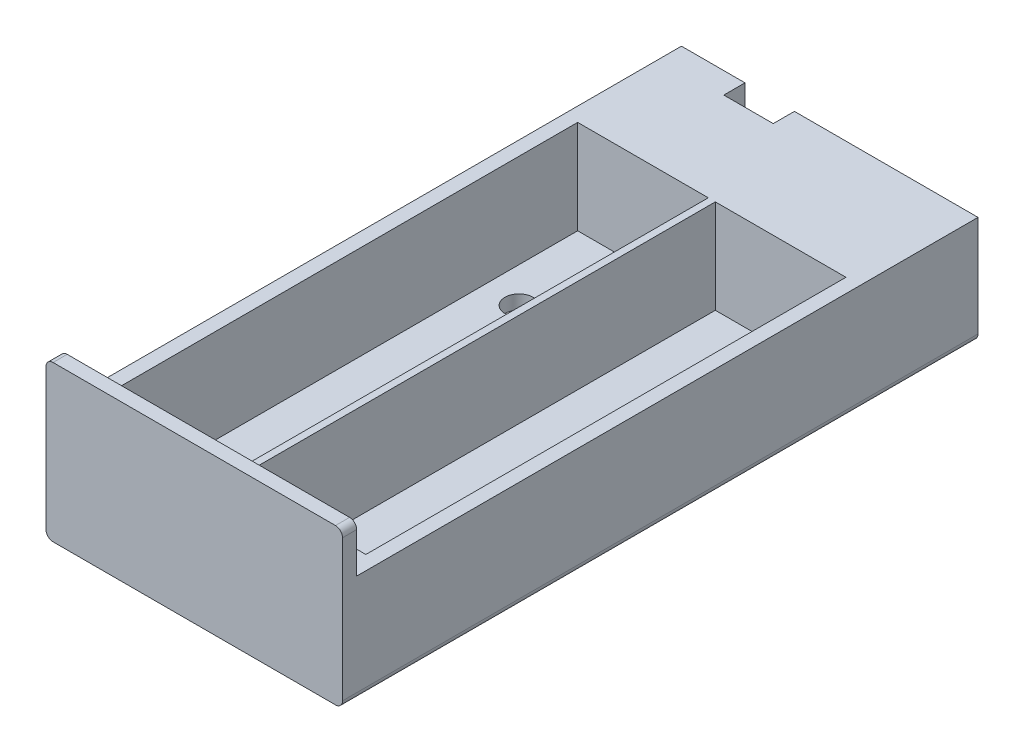
SolidWorks part; units mm, degrees
material "6061 Alloy"
ref_plane "Front" through (0, 0, 0) normal (0, 0, 1) x (1, 0, 0)
ref_plane "Top" through (0, 0, 0) normal (0, 1, 0) x (1, 0, 0)
ref_plane "Right" through (0, 0, 0) normal (1, 0, 0) x (0, 0, -1)
sketch "Sketch1" plane through (0, 0, 0) normal (0, 1, 0) x (1, 0, 0)
  line L1 (-21, -45) -> (21, -45)
  line L2 (-21, -45) -> (-21, 45)
  line L3 (-21, 45) -> (21, 45)
  line L4 (21, -45) -> (21, 45)
  line L5 (-21, -45) -> (21, 45) construction
  line L6 (-21, 45) -> (21, -45) construction
  point P0 (0, 0)
  dimension "D1" = 42
  dimension "D2" = 90
extrude "Boss-Extrude1" add sketch "Sketch1" along normal blind 22
fillet "Fillet1" radius 1 4 edges at (21, 0, 0) (-21, 0, 0) (21, 22, 0) (-21, 22, 0)
sketch "Sketch2" plane through (0, 22, 0) normal (0, 1, 0) x (1, 0, 0)
  line L0 (-20, -45) -> (20, -45) construction
  line L1 (-19, 28.3) -> (19, 28.3)
  line L2 (-19, 28.3) -> (-19, -39.7)
  line L3 (-19, -39.7) -> (19, -39.7)
  line L4 (19, 28.3) -> (19, -39.7)
  line L5 (-19, 28.3) -> (19, -39.7) construction
  line L6 (-19, -39.7) -> (19, 28.3) construction
  point P0 (0, -5.7)
  dimension "D1" = 38
  dimension "D2" = 68
  dimension "D3" = 5.3
extrude "Cut-Extrude1" cut sketch "Sketch2" against normal blind 20 contours L4 L1 L2 L3
sketch "Sketch3" plane through (0, 2, 0) normal (0, 1, 0) x (1, 0, 0)
  line L0 (-19, 28.3) -> (19, 28.3) construction
  line L1 (-0.5, 28.3) -> (0.5, 28.3)
  line L2 (-0.5, 28.3) -> (-0.5, -39.7)
  line L3 (-0.5, -39.7) -> (0.5, -39.7)
  line L4 (0.5, 28.3) -> (0.5, -39.7)
  line L5 (-19, -39.7) -> (19, -39.7) construction
  line L6 (0, 28.3) -> (0, -39.7) construction
  dimension "D1" = 1
extrude "Boss-Extrude2" add sketch "Sketch3" along normal up to surface (20 mm away) up to face at (0, 22, 0)
sketch "Sketch4" plane through (0, 22, 0) normal (0, 1, 0) x (1, 0, 0)
  line L0 (21, 45) -> (21, -45) construction
  line L1 (-21, 45) -> (21, 45)
  line L2 (-21, 45) -> (-21, -43)
  line L3 (-21, -43) -> (21, -43)
  line L4 (21, 45) -> (21, -43)
  line L5 (-20, -45) -> (20, -45) construction
  dimension "D1" = 2
extrude "Cut-Extrude2" cut sketch "Sketch4" against normal blind 6.7
sketch "Sketch5" plane through (0, 0, -45) normal (0, 0, -1) x (-1, 0, 0)
  line L0 (-21, 15.3) -> (-21, 1) construction
  line L1 (-20, 0) -> (20, 0) construction
  circle A0 centre (-13.5, 3.5) radius 1.5
  dimension "D3" = 3
  dimension "D1" = 6
  dimension "D2" = 2
extrude "Cut-Extrude3" cut sketch "Sketch5" against normal up to next
sketch "Sketch6" plane through (0, 0, -45) normal (0, 0, -1) x (-1, 0, 0)
  line L0 (-21, 15.3) -> (21, 15.3) construction
  line L1 (12, 15.3) -> (5, 15.3)
  line L2 (12, 15.3) -> (12, 10.3)
  line L3 (12, 10.3) -> (5, 10.3)
  line L4 (5, 15.3) -> (5, 10.3)
  line L5 (21, 15.3) -> (21, 1) construction
  dimension "D1" = 9
  dimension "D2" = 7
  dimension "D3" = 5
extrude "Cut-Extrude4" cut sketch "Sketch6" against normal blind 3
sketch "Sketch7" plane through (0, 0, 0) normal (0, -1, 0) x (1, 0, 0)
  line L0 (-20, 45) -> (20, 45) construction
  line L1 (14, 25) -> (-14, 25) construction
  line L2 (14, 25) -> (14, -15) construction
  line L3 (14, -15) -> (-14, -15) construction
  line L4 (-14, 25) -> (-14, -15) construction
  line L5 (14, 25) -> (-14, -15) construction
  line L6 (14, -15) -> (-14, 25) construction
  circle A0 centre (14, -15) radius 2
  circle A1 centre (14, 25) radius 2
  circle A2 centre (-14, 25) radius 2
  circle A3 centre (-14, -15) radius 2
  point P0 (0, 5)
  dimension "D1" = 4
  dimension "D2" = 28
  dimension "D3" = 40
  dimension "D4" = 20
extrude "Cut-Extrude5" cut sketch "Sketch7" against normal through all
ref_plane "Plane1" through (-9.75, 0, 0) normal (1, 0, 0) x (0, 0, -1)
ref_plane "Plane2" through (9.75, 0, 0) normal (-1, 0, 0) x (0, 0, 1)
ref_plane "Plane3" through (0, 0, 5.7) normal (0, 0, 1) x (1, 0, 0)
